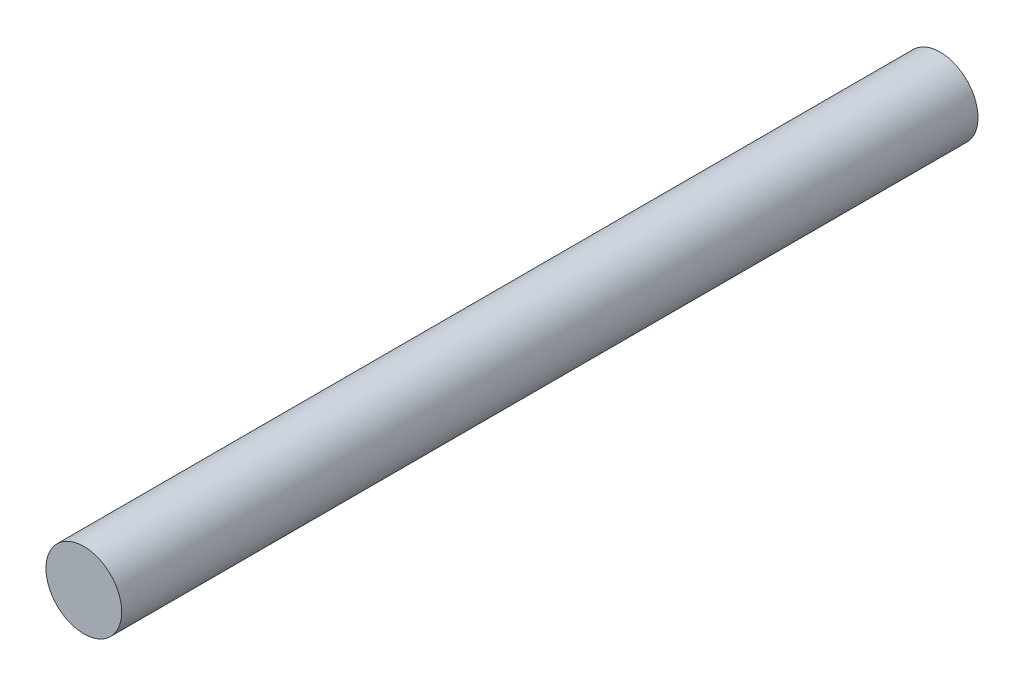
SolidWorks part; units mm, degrees
ref_plane "Front Plane" through (0, 0, 0) normal (0, 0, 1) x (1, 0, 0)
ref_plane "Top Plane" through (0, 0, 0) normal (0, 1, 0) x (1, 0, 0)
ref_plane "Right Plane" through (0, 0, 0) normal (1, 0, 0) x (0, 0, -1)
sketch "Sketch1" plane through (0, 0, 0) normal (0, 0, 1) x (1, 0, 0)
  circle A0 centre (0, 0) radius 3.175
  dimension "D1" = 6.35
extrude "Boss-Extrude1" add sketch "Sketch1" along normal blind 71.7296
